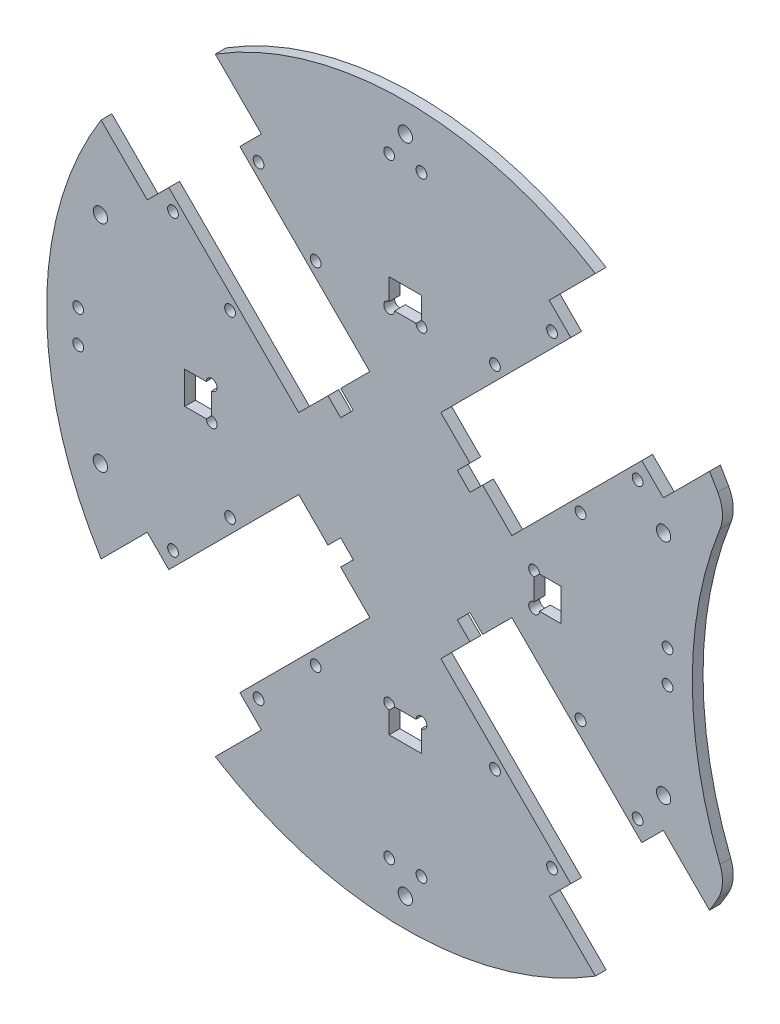
SolidWorks part; units mm, degrees
ref_plane "Alzado" through (0, 0, 0) normal (0, 0, 1) x (1, 0, 0)
ref_plane "Planta" through (0, 0, 0) normal (0, 1, 0) x (1, 0, 0)
ref_plane "Vista lateral" through (0, 0, 0) normal (1, 0, 0) x (0, 0, -1)
sketch "Croquis1" plane through (0, 0, 0) normal (0, 0, 1) x (1, 0, 0)
  circle A0 centre (0, 0) radius 100
  dimension "D1" = 200
extrude "Saliente-Extruir1" add sketch "Croquis1" along normal blind 3
sketch "Croquis3" plane through (0, 0, 3) normal (0, 0, 1) x (1, 0, 0)
  line L0 (0, 0) -> (190, 0) construction
  circle A0 centre (190, 0) radius 110
  dimension "D1" = 220
  dimension "D2" = 190
extrude "Cortar-Extruir1" cut sketch "Croquis3" against normal blind 3
fillet "Redondeo1" radius 10 2 edges at (89.4737, -44.6594, 1.5) (89.4737, 44.6594, 1.5)
sketch "Croquis5" plane through (0, 0, 3) normal (0, 0, 1) x (1, 0, 0)
  line L0 (0, -100) -> (0, 100) construction
  line L1 (-100, 0) -> (80, 0) construction
  line L2 (0, 0) -> (-70.7107, -70.7107) construction
  line L3 (-70.7107, -70.7107) -> (70.7107, 70.7107) construction
  line L4 (0, 0) -> (-70.7107, 70.7107) construction
  line L5 (-70.7107, 70.7107) -> (70.7107, -70.7107) construction
  line L6 (-29.6985, -9.8995) -> (-9.8995, -29.6985)
  line L7 (-29.6985, -9.8995) -> (-84.1457, -64.3467)
  line L8 (-9.8995, -29.6985) -> (-64.3467, -84.1457)
  line L9 (-84.1457, -64.3467) -> (-64.3467, -84.1457)
  line L10 (-9.8995, 29.6985) -> (-29.6985, 9.8995)
  line L11 (-9.8995, 29.6985) -> (-64.3467, 84.1457)
  line L12 (-64.3467, 84.1457) -> (-84.1457, 64.3467)
  line L13 (-29.6985, 9.8995) -> (-84.1457, 64.3467)
  line L14 (29.6985, 9.8995) -> (9.8995, 29.6985)
  line L15 (29.6985, 9.8995) -> (84.1457, 64.3467)
  line L16 (84.1457, 64.3467) -> (64.3467, 84.1457)
  line L17 (9.8995, 29.6985) -> (64.3467, 84.1457)
  line L18 (9.8995, -29.6985) -> (29.6985, -9.8995)
  line L19 (9.8995, -29.6985) -> (64.3467, -84.1457)
  line L20 (64.3467, -84.1457) -> (84.1457, -64.3467)
  line L21 (29.6985, -9.8995) -> (84.1457, -64.3467)
  arc A0 (87.1345, 49.0671) -> (87.1345, -49.0671) centre (0, 0) ccw construction
  arc A1 (87.7193, 40.4803) -> (87.7193, -40.4803) centre (190, 0) ccw construction
  point P36 (0, 0)
  dimension "D1" = 45
  dimension "D2" = 45
  dimension "D3" = 28
  dimension "D4" = 14
  dimension "D5" = 5
  dimension "D6" = 77
  dimension "D8" = 5
  dimension "D9" = 5
  dimension "D7" = 4
extrude "Cortar-Extruir2" cut sketch "Croquis5" against normal blind 10
sketch "Croquis7" plane through (0, 0, 3) normal (0, 0, 1) x (1, 0, 0)
  line L0 (-71.9393, -40.1195) -> (-40.1195, -71.9393)
  line L1 (-71.9393, -40.1195) -> (-88.9099, -57.0901)
  line L2 (-40.1195, -71.9393) -> (-57.0901, -88.9099)
  line L3 (-88.9099, -57.0901) -> (-57.0901, -88.9099)
  line L4 (-29.6985, -9.8995) -> (-79.9138, -60.1148) construction
  line L7 (-73, -73) -> (0, 0) construction
  line L8 (-40.1195, 71.9393) -> (-71.9393, 40.1195)
  line L9 (-40.1195, 71.9393) -> (-57.0901, 88.9099)
  line L10 (-57.0901, 88.9099) -> (-88.9099, 57.0901)
  line L11 (-71.9393, 40.1195) -> (-88.9099, 57.0901)
  line L12 (71.9393, 40.1195) -> (40.1195, 71.9393)
  line L13 (71.9393, 40.1195) -> (88.9099, 57.0901)
  line L14 (88.9099, 57.0901) -> (57.0901, 88.9099)
  line L15 (40.1195, 71.9393) -> (57.0901, 88.9099)
  line L16 (40.1195, -71.9393) -> (71.9393, -40.1195)
  line L17 (40.1195, -71.9393) -> (57.0901, -88.9099)
  line L18 (57.0901, -88.9099) -> (88.9099, -57.0901)
  line L19 (71.9393, -40.1195) -> (88.9099, -57.0901)
  line L23 (-21.5668, -18.0312) -> (-18.0312, -21.5668)
  line L24 (-21.5668, -18.0312) -> (-18.0312, -14.4957)
  line L25 (-18.0312, -21.5668) -> (-14.4957, -18.0312)
  line L26 (-18.0312, -14.4957) -> (-14.4957, -18.0312)
  line L42 (-21.5668, 18.0312) -> (-18.0312, 14.4957)
  line L43 (-18.0312, 21.5668) -> (-14.4957, 18.0312)
  line L44 (-18.0312, 21.5668) -> (-21.5668, 18.0312)
  line L45 (-14.4957, 18.0312) -> (-18.0312, 14.4957)
  line L46 (18.0312, 21.5668) -> (14.4957, 18.0312)
  line L47 (21.5668, 18.0312) -> (18.0312, 14.4957)
  line L48 (21.5668, 18.0312) -> (18.0312, 21.5668)
  line L49 (18.0312, 14.4957) -> (14.4957, 18.0312)
  line L50 (21.5668, -18.0312) -> (18.0312, -14.4957)
  line L51 (18.0312, -21.5668) -> (14.4957, -18.0312)
  line L52 (18.0312, -21.5668) -> (21.5668, -18.0312)
  line L53 (14.4957, -18.0312) -> (18.0312, -14.4957)
  arc A0 (-79.9138, 60.1148) -> (-79.9138, -60.1148) centre (0, 0) ccw construction
  arc A2 (-79.9138, 60.1148) -> (-79.9138, -60.1148) centre (0, 0) ccw construction
  point P24 (0, 0)
  point P47 (0, -3.5355)
  point P48 (0, 0)
  dimension "D1" = 90
  dimension "D2" = 45
  dimension "D3" = 24
  dimension "D4" = 73
  dimension "D5" = 360
  dimension "D6" = 4
  dimension "D7" = 79.2376
  dimension "D8" = 22.5
  dimension "D9" = 5
  dimension "D10" = 2.5
  dimension "D11" = 5
  dimension "D12" = 23
  dimension "D14" = 23
  dimension "D15" = 23
  dimension "D13" = 4
extrude "Cortar-Extruir3" cut sketch "Croquis7" against normal blind 10
sketch "Croquis8" plane through (0, 0, 3) normal (0, 0, 1) x (1, 0, 0)
  line L0 (-71.9393, 40.1195) -> (-65.9289, 46.1299) construction
  line L1 (-65.9289, 46.1299) -> (-29.6985, 9.8995) construction
  line L2 (0, 0) -> (0, 100) construction
  line L3 (-46.1299, 65.9289) -> (-40.1195, 71.9393) construction
  line L4 (52.9877, 84.8075) -> (40.1195, 71.9393) construction
  line L7 (-65.9289, -46.1299) -> (-71.9393, -40.1195) construction
  line L8 (-29.6985, -9.8995) -> (-65.9289, -46.1299) construction
  line L9 (-52.9877, -84.8075) -> (-40.1195, -71.9393) construction
  line L11 (-100, 0) -> (80, 0) construction
  line L14 (71.9393, 40.1195) -> (84.8075, 52.9877) construction
  circle A0 centre (-64.7622, 40.9044) radius 1.5
  circle A1 centre (-48.8523, 24.9945) radius 1.5023
  circle A2 centre (-24.9945, 48.8523) radius 1.5
  circle A3 centre (-40.9044, 64.7622) radius 1.5
  circle A16 centre (64.7622, 40.9044) radius 1.5
  circle A17 centre (48.8523, 24.9945) radius 1.5
  circle A18 centre (24.9945, 48.8523) radius 1.5023
  circle A19 centre (40.9044, 64.7622) radius 1.5
  circle A20 centre (40.9044, -64.7622) radius 1.5
  circle A21 centre (24.9945, -48.8523) radius 1.5
  circle A22 centre (48.8523, -24.9945) radius 1.5023
  circle A23 centre (64.7622, -40.9044) radius 1.5
  circle A24 centre (-64.7622, -40.9044) radius 1.5
  circle A25 centre (-48.8523, -24.9945) radius 1.5
  circle A26 centre (-24.9945, -48.8523) radius 1.5023
  circle A27 centre (-40.9044, -64.7622) radius 1.5
  circle A28 centre (0, 92) radius 2
  arc A29 (52.9877, 84.8075) -> (-52.9877, 84.8075) centre (0, 0) ccw construction
  circle A32 centre (0, -92) radius 2
  arc A35 (-52.9877, -84.8075) -> (52.9877, -84.8075) centre (0, 0) ccw construction
  arc A36 (-84.8075, 52.9877) -> (-84.8075, -52.9877) centre (0, 0) ccw construction
  arc A38 (87.7193, 40.4803) -> (87.7193, -40.4803) centre (190, 0) ccw construction
  circle A44 centre (72, 31.6949) radius 2
  circle A45 centre (72, -31.6949) radius 2
  circle A46 centre (-85, -30) radius 2
  circle A47 centre (-85, 30) radius 2
  point P41 (0, 0)
  dimension "D1" = 3
  dimension "D2" = 22.5
  dimension "D3" = 33.74
  dimension "D4" = 3.0046
  dimension "D5" = 33.74
  dimension "D6" = 27.02
  dimension "D7" = 3
  dimension "D8" = 3
  dimension "D9" = 2.87
  dimension "D10" = 22.5
  dimension "D11" = 2.87
  dimension "D12" = 27.02
  dimension "D14" = 4.52
  dimension "D15" = 2.87
  dimension "D16" = 4
  dimension "D17" = 92
  dimension "D18" = 42.5538
  dimension "D21" = 92
  dimension "D22" = 42.5538
  dimension "D19" = 4
  dimension "D20" = 4
  dimension "D23" = 6
  dimension "D24" = 72
  dimension "D25" = 4
  dimension "D26" = 4
  dimension "D27" = 30
  dimension "D28" = 85
  dimension "D29" = 30
  dimension "D30" = 85
  dimension "D13" = 4
extrude "Cortar-Extruir4" cut sketch "Croquis8" against normal blind 10
sketch "Croquis9" plane through (0, 0, 3) normal (0, 0, 1) x (1, 0, 0)
  line L0 (-100, 0) -> (80, 0) construction
  line L5 (0, -100) -> (0, 100) construction
  line L6 (37.6, 3.75) -> (42.1, 3.75)
  line L7 (37.6, 3.75) -> (37.6, -3.75)
  line L8 (37.6, -3.75) -> (42.1, -3.75)
  line L9 (42.1, 3.75) -> (42.1, -3.75)
  line L10 (-3.75, -49.5) -> (3.75, -49.5)
  line L11 (-55.6901, 3.75) -> (-60.1901, 3.75)
  line L12 (-55.6901, 3.75) -> (-55.6901, -3.75)
  line L13 (-55.6901, -3.75) -> (-60.1901, -3.75)
  line L14 (-60.1901, 3.75) -> (-60.1901, -3.75)
  line L15 (-3.75, 54) -> (3.75, 54)
  line L16 (-3.75, 54) -> (-3.75, 49.5)
  line L17 (-3.75, 49.5) -> (3.75, 49.5)
  line L18 (3.75, 54) -> (3.75, 49.5)
  line L19 (3.75, -54) -> (3.75, -49.5)
  line L20 (-3.75, -54) -> (3.75, -54)
  line L21 (-3.75, -54) -> (-3.75, -49.5)
  circle A0 centre (73.1, -4.5) radius 1.5
  circle A1 centre (35.9, 4.5) radius 1.5
  arc A2 (-84.8075, 52.9877) -> (-84.8075, -52.9877) centre (0, 0) ccw construction
  arc A3 (87.7193, 40.4803) -> (87.7193, -40.4803) centre (190, 0) ccw construction
  circle A4 centre (73.1, 4.5) radius 1.5
  circle A5 centre (35.9, -4.5) radius 1.5
  arc A6 (-52.9877, -84.8075) -> (52.9877, -84.8075) centre (0, 0) ccw construction
  arc A7 (52.9877, 84.8075) -> (-52.9877, 84.8075) centre (0, 0) ccw construction
  circle A8 centre (-91.1901, 4.5) radius 1.5
  circle A9 centre (-91.1901, -4.5) radius 1.5
  circle A10 centre (-53.9901, 4.5) radius 1.5
  circle A11 centre (-53.9901, -4.5) radius 1.5
  circle A12 centre (-4.5, 85) radius 1.5
  circle A13 centre (4.5, 85) radius 1.5
  circle A14 centre (-4.5, 47.8) radius 1.5
  circle A15 centre (4.5, 47.8) radius 1.5
  circle A20 centre (-4.5, -47.8) radius 1.5
  circle A21 centre (4.5, -47.8) radius 1.5
  circle A22 centre (4.5, -85) radius 1.5
  circle A23 centre (-4.5, -85) radius 1.5
  dimension "D6" = 35.9
  dimension "D7" = 3
  dimension "D8" = 37.2
  dimension "D9" = 37.2
  dimension "D10" = 3
  dimension "D11" = 3
  dimension "D12" = 4.5
  dimension "D13" = 4.5
  dimension "D14" = 3
  dimension "D15" = 3
  dimension "D16" = 3
  dimension "D3" = 35.9
  dimension "D21" = 4.5
  dimension "D22" = 4.5
  dimension "D23" = 3
  dimension "D24" = 3
  dimension "D25" = 4.5
  dimension "D26" = 4.5
  dimension "D27" = 37.2
  dimension "D28" = 37.2
  dimension "D29" = 91.1901
  dimension "D30" = 91.1901
  dimension "D35" = 3
  dimension "D36" = 3
  dimension "D37" = 4.5
  dimension "D38" = 4.5
  dimension "D39" = 3
  dimension "D40" = 3
  dimension "D41" = 4.5
  dimension "D42" = 4.5
  dimension "D43" = 37.2
  dimension "D44" = 37.2
  dimension "D45" = 85
  dimension "D46" = 85
  dimension "D51" = 4.5
  dimension "D52" = 4.5
  dimension "D17" = 4.5
  dimension "D18" = 7.5
  dimension "D19" = 1.7
  dimension "D20" = 0.75
  dimension "D31" = 7.5
  dimension "D32" = 4.5
  dimension "D33" = 1.7
  dimension "D34" = 0.75
  dimension "D47" = 7.5
  dimension "D48" = 4.5
  dimension "D49" = 0.75
  dimension "D50" = 1.7
extrude "Cortar-Extruir5" cut sketch "Croquis9" against normal blind 10
sketch "Croquis10" plane through (0, 0, 3) normal (0, 0, 1) x (1, 0, 0)
  line L0 (-55.4901, 4.5) -> (-61.4901, 4.5)
  line L1 (-61.4901, 4.5) -> (-61.4901, -4.5)
  line L2 (-61.4901, -4.5) -> (-55.4901, -4.5)
  line L3 (-53.9901, 3) -> (-53.9901, -3)
  line L4 (-9.8995, 29.6985) -> (9.8995, 29.6985) construction
  line L5 (9.8995, 29.6985) -> (0, 29.6985) construction
  line L6 (-9.8995, -29.6985) -> (9.8995, -29.6985) construction
  line L7 (9.8995, -29.6985) -> (0, -29.6985) construction
  line L8 (0, -29.6985) -> (0, 29.6985) construction
  line L9 (-29.6985, 9.8995) -> (-29.6985, -9.8995) construction
  line L10 (29.6985, 9.8995) -> (29.6985, -9.8995) construction
  line L11 (29.6985, 0) -> (-29.6985, 0) construction
  line L12 (35.9, 3) -> (35.9, -3)
  line L13 (37.4, -4.5) -> (43.4, -4.5)
  line L14 (43.4, -4.5) -> (43.4, 4.5)
  line L15 (43.4, 4.5) -> (37.4, 4.5)
  line L16 (-3, -47.8) -> (3, -47.8)
  line L17 (-4.5, -49.3) -> (-4.5, -55.3)
  line L18 (-4.5, -55.3) -> (4.5, -55.3)
  line L19 (4.5, -55.3) -> (4.5, -49.3)
  line L20 (4.5, 55.3) -> (4.5, 49.3)
  line L21 (-4.5, 55.3) -> (4.5, 55.3)
  line L22 (-4.5, 49.3) -> (-4.5, 55.3)
  line L23 (-3, 47.8) -> (3, 47.8)
  circle A0 centre (-53.9901, 4.5) radius 1.5 construction
  circle A1 centre (-53.9901, -4.5) radius 1.5 construction
  circle A2 centre (35.9, 4.5) radius 1.5 construction
  circle A3 centre (35.9, -4.5) radius 1.5 construction
  circle A4 centre (-4.5, -47.8) radius 1.5 construction
  circle A5 centre (4.5, -47.8) radius 1.5 construction
  arc A6 (-4.5, -49.3) -> (-3, -47.8) centre (-4.5, -47.8) ccw
  arc A7 (3, -47.8) -> (4.5, -49.3) centre (4.5, -47.8) ccw
  arc A8 (3, 47.8) -> (4.5, 49.3) centre (4.5, 47.8) cw
  arc A9 (-4.5, 49.3) -> (-3, 47.8) centre (-4.5, 47.8) cw
  arc A10 (-55.4901, 4.5) -> (-53.9901, 3) centre (-53.9901, 4.5) ccw
  arc A11 (-55.4901, -4.5) -> (-53.9901, -3) centre (-53.9901, -4.5) cw
  arc A12 (35.9, -3) -> (37.4, -4.5) centre (35.9, -4.5) cw
  arc A13 (37.4, 4.5) -> (35.9, 3) centre (35.9, 4.5) cw
  dimension "D1" = 6
  dimension "D2" = 6
  dimension "D3" = 6
extrude "Cortar-Extruir6" cut sketch "Croquis10" against normal blind 3 contours L22 A9 L23 A8 L20 L21 | L15 A13 L12 A12 L13 L14 | A7 L16 A6 L17 L18 L19 | L2 A11 L3 A10 L0 L1
